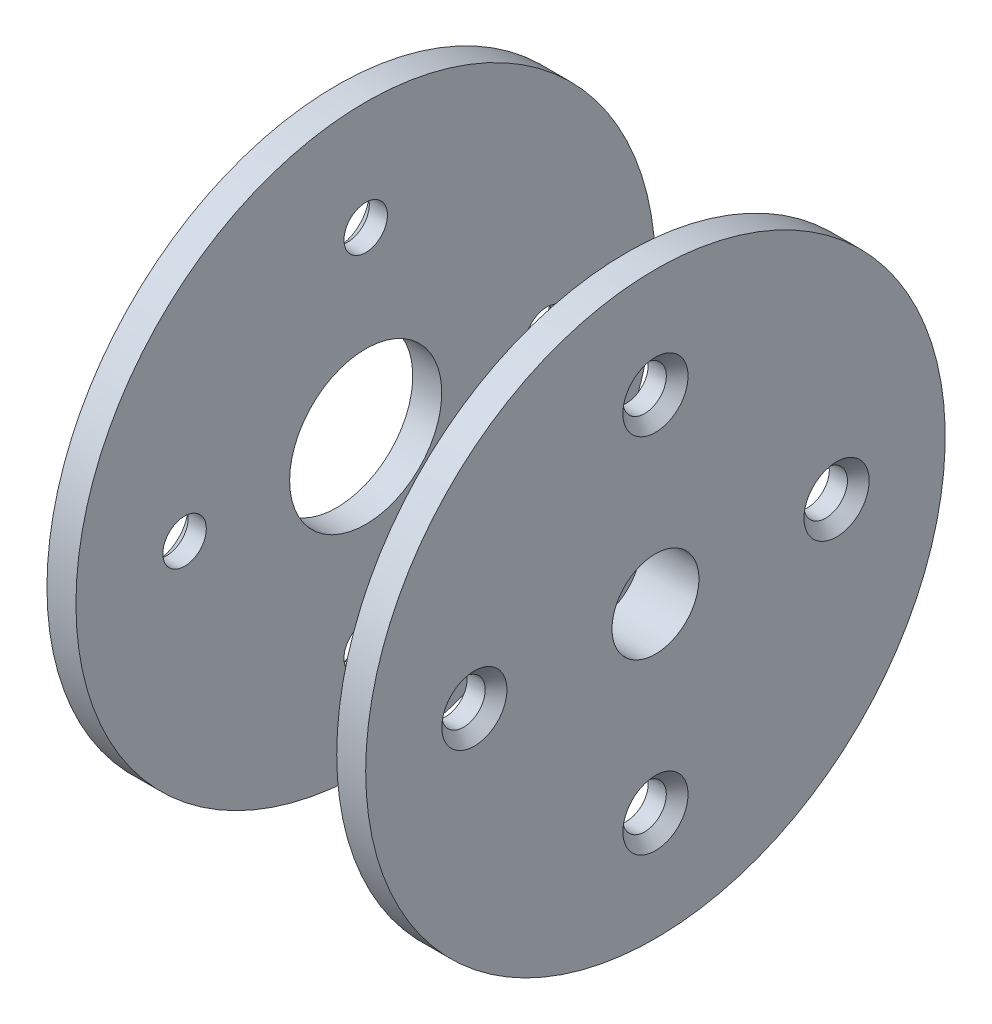
SolidWorks part; units mm, degrees
ref_plane "Front Plane" through (0, 0, 0) normal (0, 0, 1) x (1, 0, 0)
ref_plane "Top Plane" through (0, 0, 0) normal (0, 1, 0) x (1, 0, 0)
ref_plane "Right Plane" through (0, 0, 0) normal (1, 0, 0) x (0, 0, -1)
sketch "Sketch1" plane through (0, 0, 0) normal (0, 0, 1) x (1, 0, 0)
  line L0 (0, 0) -> (66.9381, 0) construction
  line L1 (0, 10.5) -> (11, 10.5)
  line L2 (11, 10.5) -> (11, 40)
  line L3 (11, 40) -> (15, 40)
  line L4 (15, 40) -> (15, 6)
  line L5 (15, 6) -> (7, 6)
  line L6 (7, 6) -> (7, 3.25)
  line L7 (7, 3.25) -> (0, 3.25)
  line L8 (0, 3.25) -> (0, 10.5)
  line L9 (-29, 10.5) -> (-29, 40)
  line L10 (-29, 40) -> (-25, 40)
  line L11 (-25, 40) -> (-25, 10.5)
  line L12 (-25, 10.5) -> (-29, 10.5)
  dimension "D1" = 6.5
  dimension "D2" = 21
  dimension "D3" = 11
  dimension "D4" = 4
  dimension "D5" = 12
  dimension "D6" = 8
  dimension "D7" = 80
  dimension "D9" = 25
revolve "Revolve1" add sketch "Sketch1" angle 360 about L0
sketch "Sketch2" plane through (15, 0, 0) normal (1, 0, 0) x (0, 0, -1)
  circle A0 centre (0, 0) radius 25 construction
  circle A1 centre (25, 0) radius 3
  circle A2 centre (0, -25) radius 3
  circle A3 centre (-25, 0) radius 3
  circle A4 centre (0, 25) radius 3
  point P14 (0, 0)
  dimension "D2" = 50
  dimension "D3" = 6
  dimension "D1" = 4
extrude "Cut-Extrude1" cut sketch "Sketch2" against normal through all
chamfer "Chamfer1" distance 1.5 angle 45 4 edges at (15, -25, -3) (15, 0, 22) (15, 0, -28) (15, 25, -3)
chamfer "Chamfer2" distance 1.5 angle 45 4 edges at (-29, 0, -28) (-29, -25, -3) (-29, 0, 22) (-29, 25, -3)
